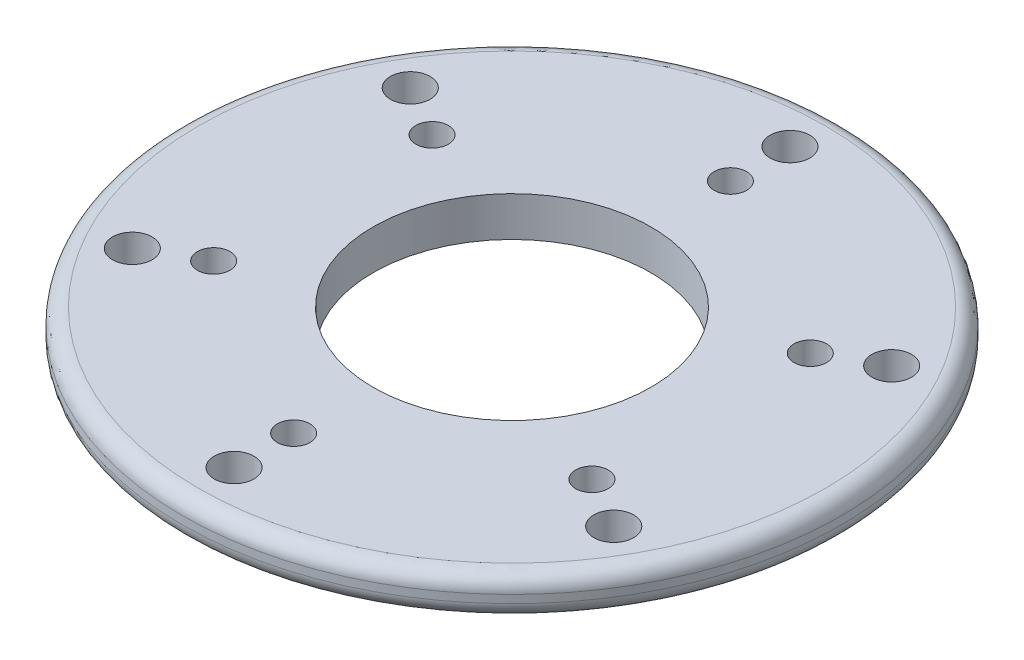
SolidWorks part; units mm, degrees
ref_plane "Ebene vorne" through (0, 0, 0) normal (0, 0, 1) x (1, 0, 0)
ref_plane "Ebene oben" through (0, 0, 0) normal (0, 1, 0) x (1, 0, 0)
ref_plane "Ebene rechts" through (0, 0, 0) normal (1, 0, 0) x (0, 0, -1)
sketch "Sketch1" plane through (0, 0, 0) normal (0, 1, 0) x (1, 0, 0)
  circle A0 centre (0, 0) radius 41.5
  dimension "D1" = 83
extrude "Main Plate" add sketch "Sketch1" along normal blind 5
sketch "Sketch2" plane through (0, 5, 0) normal (0, 1, 0) x (1, 0, 0)
  line L0 (0, 0) -> (0, 41.5) construction
  circle A1 centre (0, 0) radius 41.5 construction
  circle A2 centre (0, 27.5) radius 2.05
  circle A3 centre (23.8157, 13.75) radius 2.05
  circle A4 centre (23.8157, -13.75) radius 2.05
  circle A5 centre (0, -27.5) radius 2.05
  circle A6 centre (-23.8157, -13.75) radius 2.05
  circle A7 centre (-23.8157, 13.75) radius 2.05
  point P20 (0, 0)
  dimension "D1" = 27.5
  dimension "D2" = 4.1
extrude "G27" cut sketch "Sketch2" against normal through all
sketch "Sketch3" plane through (0, 5, 0) normal (0, 1, 0) x (1, 0, 0)
  line L0 (0, 0) -> (0, 41.5) construction
  circle A0 centre (0, 0) radius 41.5 construction
  circle A1 centre (0, 35) radius 2.5
  circle A3 centre (30.3109, 17.5) radius 2.5
  circle A4 centre (30.3109, -17.5) radius 2.5
  circle A5 centre (0, -35) radius 2.5
  circle A6 centre (-30.3109, -17.5) radius 2.5
  circle A7 centre (-30.3109, 17.5) radius 2.5
  point P22 (0, 0)
  dimension "D3" = 5
  dimension "D1" = 35
  dimension "D2" = 6
extrude "Momo - Sparko" cut sketch "Sketch3" against normal through all
sketch "Sketch4" plane through (0, 5, 0) normal (0, 1, 0) x (1, 0, 0)
  circle A0 centre (0, 0) radius 17.5
  dimension "D1" = 35
extrude "Center Hole" cut sketch "Sketch4" against normal through all
fillet "Fillet1" radius 2 1 edges at (0, 5, 41.5)
fillet "Fillet2" radius 2 1 edges at (0, 0, 41.5)
